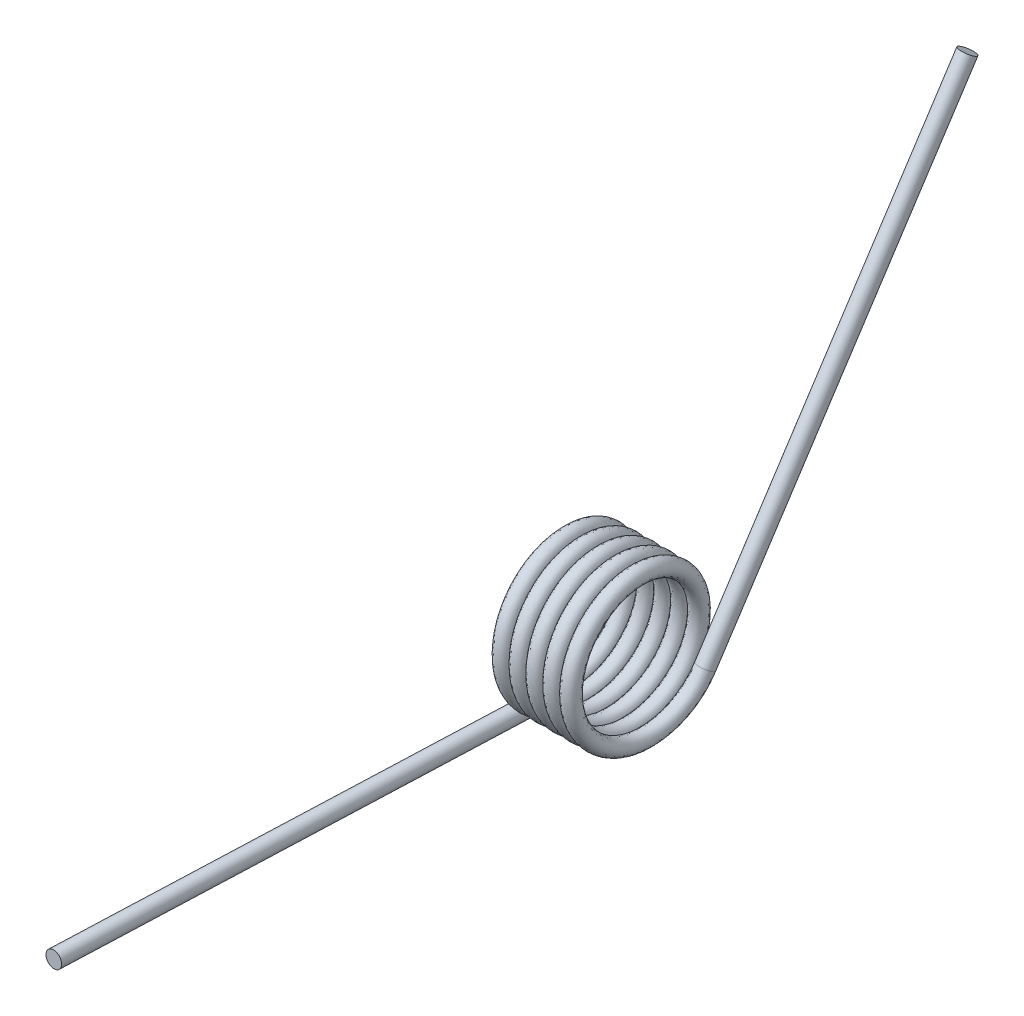
SolidWorks part; units mm, degrees
ref_plane "Front" through (0, 0, 0) normal (0, 0, 1) x (1, 0, 0)
ref_plane "Top" through (0, 0, 0) normal (0, 1, 0) x (1, 0, 0)
ref_plane "Right" through (0, 0, 0) normal (1, 0, 0) x (0, 0, -1)
sketch "Sketch1" plane through (0, 0, 0) normal (1, 0, 0) x (0, 0, -1)
  line L0 (0, -2.3495) -> (0, -2.9845) construction
  line L1 (2.5847, -1.4923) -> (12.1097, 15.0055) construction
  line L2 (0, -2.9845) -> (-19.05, -2.9845) construction
  line L3 (0, 0) -> (2.9845, 0) construction
  line L4 (0, 0) -> (2.5847, -1.4923) construction
  line L5 (-19.05, -2.9845) -> (-19.05, -2.3495) construction
  line L6 (-19.05, -2.3495) -> (0, -2.3495) construction
  line L7 (12.1097, 15.0055) -> (11.5597, 15.323) construction
  line L8 (11.5597, 15.323) -> (2.0347, -1.1748) construction
  circle A0 centre (0, 0) radius 2.9845 construction
  circle A1 centre (0, 0) radius 1.778 construction
  circle A2 centre (0, 0) radius 2.667 construction
  point P7 (0, -2.667)
  point P10 (0, 2.9845)
  dimension "OD" = 5.969
  dimension "For Shaft Diameter" = 3.556
  dimension "Wire Diameter" = 0.635
  dimension "Leg Length" = 19.05
  dimension "Deflection Angle" = 120
sketch "Sketch2" plane through (0, 0, 0) normal (1, 0, 0) x (0, 0, -1)
  circle A0 centre (0, 0) radius 2.667 construction
  circle A2 centre (0, 0) radius 2.667
curve "Helix/Spiral1" pitch 0.6604 height 3.4121 turns 5.1667
ref_plane "Plane1" through (0, -2.667, 0) normal (0.0394, 0, -0.9992) x (0.999, -0.0232, 0.0394)
sketch "Sketch3" plane through (0, -2.667, 0) normal (0.0394, 0, -0.9992) x (0.999, -0.0232, 0.0394)
  circle A0 centre (0, 0) radius 0.3175
  dimension "D1" = 0.635
sweep "Sweep1" add profiles "Sketch3" path "Helix/Spiral1"
sketch "Sketch4" plane through (0, 0, 0) normal (-0.0394, 0, 0.9992) x (-0.999, 0.0232, -0.0394)
  circle A1 centre (-0.062, 2.6663) radius 0.3175
  circle A2 centre (-0.062, 2.6663) radius 0.3175
  dimension "D1" = 0
extrude "Extrude1" add sketch "Sketch4" along normal blind 19.05
sketch "Sketch5" plane through (0.0053, 0.1163, -0.0671) normal (0.0394, 0.8654, -0.4996) x (0.9982, -0.057, -0.02)
  circle A1 centre (3.5279, 2.5081) radius 0.3175
  circle A2 centre (3.5279, 2.5081) radius 0.3175
  dimension "D1" = 0
extrude "Extrude2" add sketch "Sketch5" along normal blind 19.05
sketch "Sketch6" plane through (0, 0, 0) normal (1, 0, 0) x (0, 0, -1)
  circle A2 centre (0, 0) radius 2.3495 construction
equation "\"D4@Helix/Spiral1\" = \"Wire Diameter@Sketch1\" + .001"
equation "\"D1@Sketch3\"=\"Wire Diameter@Sketch1\""
equation "\"D1@Extrude2\"=\"Leg Length@Sketch1\""
equation "\"Leg Length@Extrude1\"=\"Leg Length@Sketch1\""
